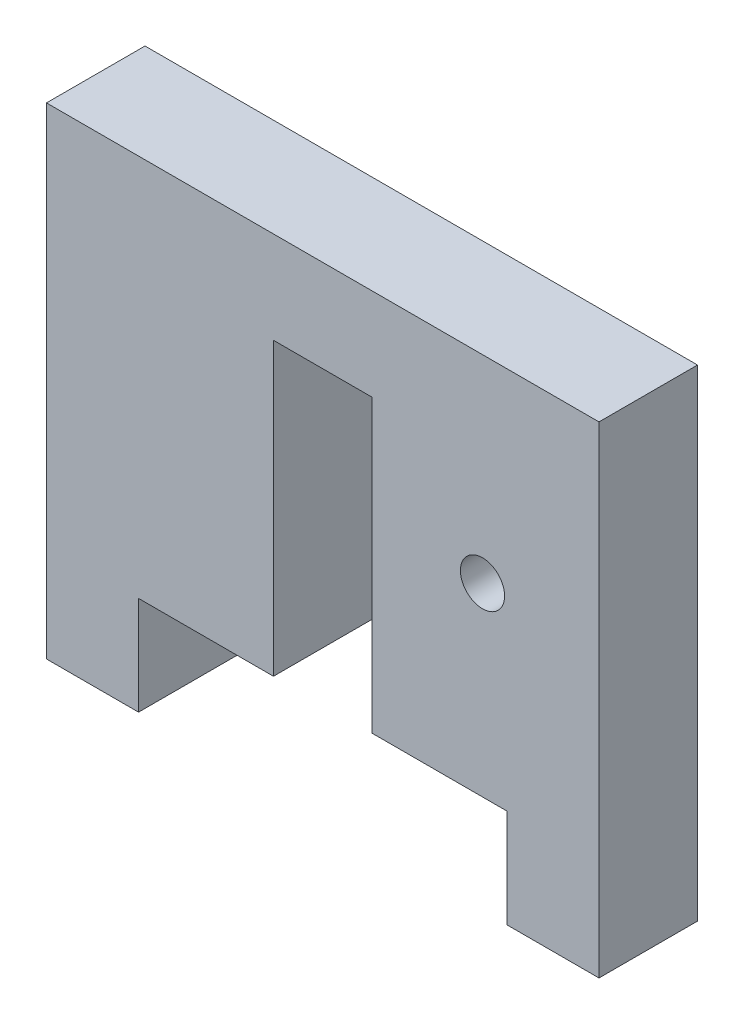
SolidWorks part; units mm, degrees
ref_plane "Front Plane" through (0, 0, 0) normal (0, 0, 1) x (1, 0, 0)
ref_plane "Top Plane" through (0, 0, 0) normal (0, 1, 0) x (1, 0, 0)
ref_plane "Right Plane" through (0, 0, 0) normal (1, 0, 0) x (0, 0, -1)
sketch "Model" plane through (0, 0, 0) normal (0, 0, 1) x (1, 0, 0)
  line L284 (30, 26.15) -> (30, 0)
  line L285 (0, 26.15) -> (30, 26.15)
  line L286 (0, 0) -> (0, 26.15)
  line L287 (5, 0) -> (0, 0)
  line L288 (5, 5.35) -> (5, 0)
  line L289 (12.325, 5.35) -> (5, 5.35)
  line L290 (12.325, 21.15) -> (12.325, 5.35)
  line L291 (17.675, 21.15) -> (12.325, 21.15)
  line L292 (17.675, 5.35) -> (17.675, 21.15)
  line L293 (25, 5.35) -> (17.675, 5.35)
  line L294 (25, 0) -> (25, 5.35)
  line L295 (30, 0) -> (25, 0)
  circle A25 centre (23.675, 15.4) radius 1.2
extrude "Boss-Extrude1" add sketch "Model" along normal blind 5.35
